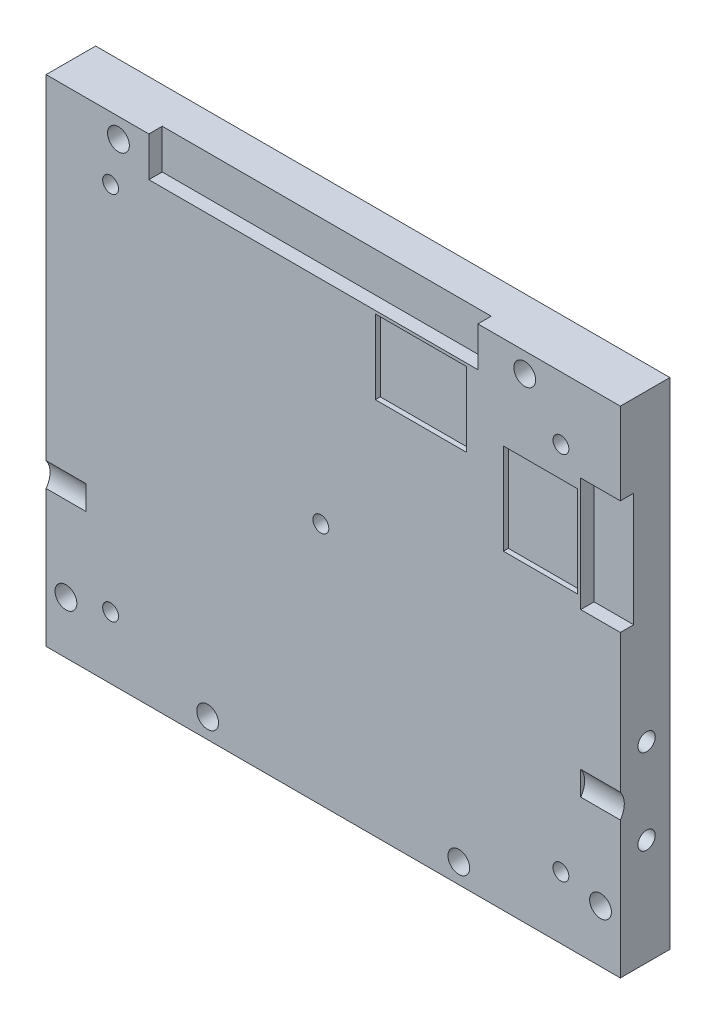
SolidWorks part; units mm, degrees
material "6061-T6 (SS)"
ref_plane "前视基准面" through (0, 0, 0) normal (0, 0, 1) x (1, 0, 0)
ref_plane "上视基准面" through (0, 0, 0) normal (0, 1, 0) x (1, 0, 0)
ref_plane "右视基准面" through (0, 0, 0) normal (1, 0, 0) x (0, 0, -1)
other "Configuration Table"
sketch "草图1" plane through (0, 0, 0) normal (0, 0, 1) x (1, 0, 0)
  line L1 (-4.3, -4.3) -> (53.65, -4.3)
  line L2 (-4.3, -4.3) -> (-4.3, 45.68)
  line L3 (-4.3, 45.68) -> (53.65, 45.68)
  line L4 (53.65, -4.3) -> (53.65, 45.68)
  dimension "D1" = 53.65
  dimension "D2" = 4.3
  dimension "D3" = 45.68
  dimension "D4" = 4.3
extrude "Main_Stock" add sketch "草图1" along normal blind 5 from offset 2.7519
sketch "草图2" plane through (0, 0, 2.2481) normal (0, 0, 1) x (1, 0, 0)
  circle A0 centre (-2.3, 1) radius 1.1
  circle A1 centre (51.65, 1) radius 1.1
  circle A2 centre (12, -2.3) radius 1.1
  circle A3 centre (37.35, -2.3) radius 1.1
  circle A4 centre (3, 43.68) radius 1.1
  circle A5 centre (44, 43.68) radius 1.1
  dimension "D1" = 2.2
  dimension "D2" = 3
  dimension "D3" = 12
  dimension "D4" = 37.35
  dimension "D5" = 44
  dimension "D6" = 51.65
  dimension "D7" = 2.3
  dimension "D8" = 1
  dimension "D9" = 43.68
  dimension "D10" = 2.3
extrude "Frame_6xD2p2_Through" cut sketch "草图2" against normal through all
sketch "草图3" plane through (0, 0, 2.2481) normal (0, 0, 1) x (1, 0, 0)
  circle A0 centre (23.4283, 20.2768) radius 0.8
  circle A1 centre (2.2063, 39.3338) radius 0.8
  circle A2 centre (47.6533, 39.3338) radius 0.8
  circle A3 centre (47.6533, 1.9767) radius 0.8
  circle A4 centre (2.2063, 1.9767) radius 0.8
  dimension "D1" = 1.6
  dimension "D2" = 2.2063
  dimension "D3" = 23.4283
  dimension "D4" = 47.6533
  dimension "D5" = 1.9767
  dimension "D6" = 20.2768
  dimension "D7" = 39.3338
extrude "PCB_5xD1p6_M2_Through" cut sketch "草图3" against normal through all
cosmetic thread "PCB_M2_Cosmetic_1" parameters "D2"=2
cosmetic thread "PCB_M2_Cosmetic_2" parameters "D2"=2
cosmetic thread "PCB_M2_Cosmetic_3" parameters "D2"=2
cosmetic thread "PCB_M2_Cosmetic_4" parameters "D2"=2
cosmetic thread "PCB_M2_Cosmetic_5" parameters "D2"=2
sketch "草图4" plane through (-4.3, 0, 0) normal (-1, 0, 0) x (0, 0, 1)
  circle A0 centre (3.8995, 10.725) radius 2.05
  dimension "D1" = 4.1
  dimension "D2" = 3.8995
  dimension "D3" = 10.725
extrude "SMA_L_Center_Matching_Arc" cut sketch "草图4" against normal blind 4
sketch "草图5" plane through (-4.3, 0, 0) normal (-1, 0, 0) x (0, 0, 1)
  circle A0 centre (-0.4005, 6.425) radius 0.875
  circle A1 centre (-0.4005, 15.025) radius 0.875
  dimension "D1" = 1.75
  dimension "D2" = 0.4005
  dimension "D3" = 6.425
  dimension "D4" = 15.025
extrude "SMA_L_Lower_2xD1p75_Blind4" cut sketch "草图5" against normal blind 4
cosmetic thread "SMA_L_Lower_Cosmetic_1" parameters "D1"=3.5, "D2"=2.2
cosmetic thread "SMA_L_Lower_Cosmetic_2" parameters "D1"=3.5, "D2"=2.2
sketch "草图6" plane through (53.65, 0, 0) normal (1, 0, 0) x (0, 0, -1)
  circle A0 centre (-3.8995, 10.725) radius 2.05
  dimension "D1" = 4.1
  dimension "D2" = 3.8995
  dimension "D3" = 10.725
extrude "SMA_R_Center_Matching_Arc" cut sketch "草图6" against normal blind 4
sketch "草图7" plane through (53.65, 0, 0) normal (1, 0, 0) x (0, 0, -1)
  circle A0 centre (0.4005, 6.425) radius 0.875
  circle A1 centre (0.4005, 15.025) radius 0.875
  dimension "D1" = 1.75
  dimension "D2" = 0.4005
  dimension "D3" = 6.425
  dimension "D4" = 15.025
extrude "SMA_R_Lower_2xD1p75_Blind4" cut sketch "草图7" against normal blind 4
cosmetic thread "SMA_R_Lower_Cosmetic_1" parameters "D1"=3.5, "D2"=2.2
cosmetic thread "SMA_R_Lower_Cosmetic_2" parameters "D1"=3.5, "D2"=2.2
sketch "草图8" plane through (53.65, 0, 0) normal (1, 0, 0) x (0, 0, -1)
  line L1 (-0.9, 25.9) -> (-7.6, 25.9)
  line L2 (-0.9, 25.9) -> (-0.9, 37.4)
  line L3 (-0.9, 37.4) -> (-7.6, 37.4)
  line L4 (-7.6, 25.9) -> (-7.6, 37.4)
  dimension "D1" = 0.9
  dimension "D2" = 7.6
  dimension "D3" = 25.9
  dimension "D4" = 37.4
extrude "Right_TypeC_Window_Lower" cut sketch "草图8" against normal blind 4
sketch "草图9" plane through (0, 45.68, 0) normal (0, 1, 0) x (1, 0, 0)
  line L1 (6.07, -0.9) -> (39.273, -0.9)
  line L2 (6.07, -0.9) -> (6.07, -7.6)
  line L3 (6.07, -7.6) -> (39.273, -7.6)
  line L4 (39.273, -0.9) -> (39.273, -7.6)
  dimension "D1" = 6.07
  dimension "D2" = 39.273
  dimension "D3" = 0.9
  dimension "D4" = 7.6
extrude "Rear_Window_Lower" cut sketch "草图9" against normal blind 4
sketch "草图10" plane through (0, 0, 2.2481) normal (0, 0, 1) x (1, 0, 0)
  line L1 (41.85, 27.1) -> (49.35, 27.1)
  line L2 (41.85, 27.1) -> (41.85, 36.3)
  line L3 (41.85, 36.3) -> (49.35, 36.3)
  line L4 (49.35, 27.1) -> (49.35, 36.3)
  dimension "D1" = 41.85
  dimension "D2" = 49.35
  dimension "D3" = 27.1
  dimension "D4" = 36.3
extrude "TypeC_Bottom_Recess_A" cut sketch "草图10" against normal blind 0.5
sketch "草图11" plane through (0, 0, 2.2481) normal (0, 0, 1) x (1, 0, 0)
  line L1 (28.923, 33.88) -> (38.123, 33.88)
  line L2 (28.923, 33.88) -> (28.923, 41.38)
  line L3 (28.923, 41.38) -> (38.123, 41.38)
  line L4 (38.123, 33.88) -> (38.123, 41.38)
  dimension "D1" = 28.923
  dimension "D2" = 38.123
  dimension "D3" = 33.88
  dimension "D4" = 41.38
extrude "TypeC_Bottom_Recess_B" cut sketch "草图11" against normal blind 0.5
